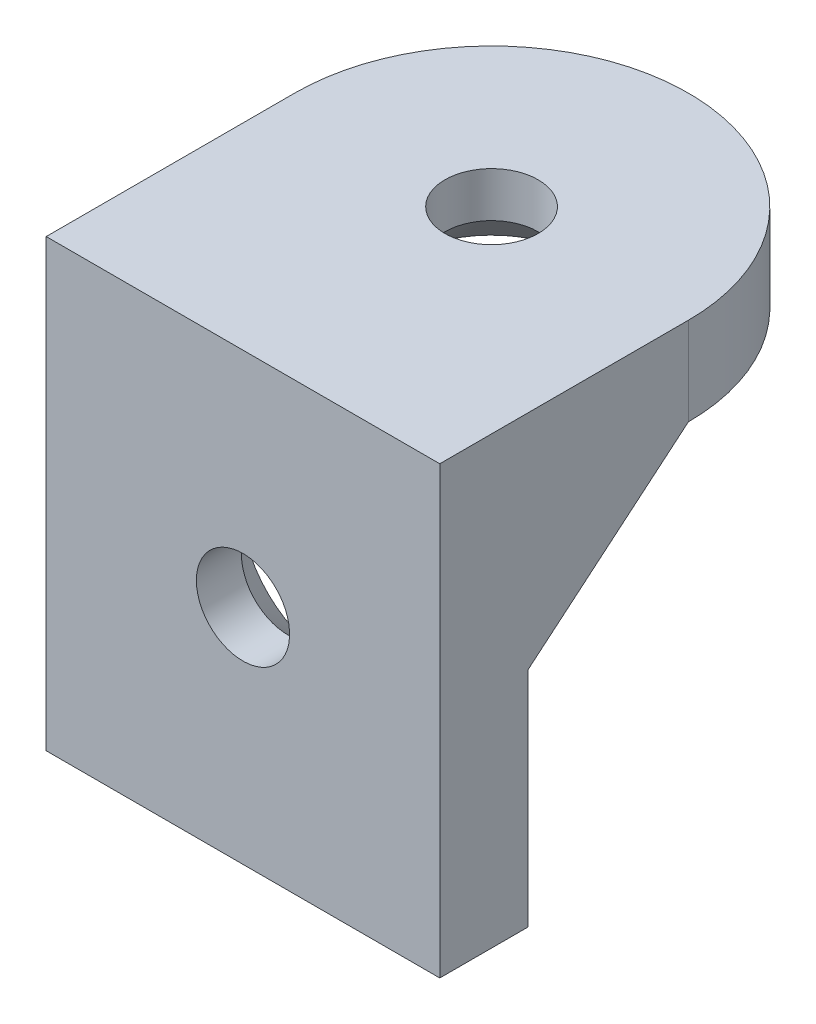
SolidWorks part; units mm, degrees
ref_plane "前视基准面" through (0, 0, 0) normal (0, 0, 1) x (1, 0, 0)
ref_plane "上视基准面" through (0, 0, 0) normal (0, 1, 0) x (1, 0, 0)
ref_plane "右视基准面" through (0, 0, 0) normal (1, 0, 0) x (0, 0, -1)
sketch "草图1" plane through (0, 0, 0) normal (0, 0, 1) x (1, 0, 0)
  line L1 (-19, -21.5) -> (19, -21.5)
  line L2 (-19, -21.5) -> (-19, 21.5)
  line L3 (-19, 21.5) -> (19, 21.5)
  line L4 (19, -21.5) -> (19, 21.5)
  line L5 (-19, -21.5) -> (19, 21.5) construction
  line L6 (-19, 21.5) -> (19, -21.5) construction
  point P0 (0, 0)
  dimension "D1" = 38
  dimension "D2" = 43
extrude "凸台-拉伸1" add sketch "草图1" along normal blind 8.5
sketch "草图2" plane through (0, 21.5, 0) normal (0, 1, 0) x (1, 0, 0)
  line L0 (-19, -8.5) -> (19, -8.5)
  line L1 (-19, -8.5) -> (-19, 15.5)
  line L2 (19, -8.5) -> (19, 15.5)
  arc A0 (-19, 15.5) -> (19, 15.5) centre (0, 15.5) cw
  dimension "D1" = 24
extrude "凸台-拉伸2" add sketch "草图2" against normal blind 8.5
sketch "草图5" plane through (19, 0, 0) normal (1, 0, 0) x (0, 0, -1)
  line L0 (15.5, 13) -> (0, 13)
  line L1 (0, 13) -> (0, 0)
  line L2 (0, 0) -> (15.5, 13)
extrude "凸台-拉伸3" add sketch "草图5" against normal blind 3.8
mirror "镜向1" about plane through (0, 0, 0) normal (1, 0, 0) of "凸台-拉伸3"
hole_wizard "M8 平锥沉头螺钉的锥形沉头孔1" positions "草图7" profile "草图6" countersink size "M8" standard "JIS" end condition through all
sketch "草图7" plane through (0, 0, 0) normal (0, 0, -1) x (-1, 0, 0)
  point P0 (0, 0)
sketch "草图6" plane through (0, 0, 0) normal (1, 0, 0) x (0, 1, 0)
  line L0 (0, 0) -> (0, 8.5)
  line L1 (0, 8.5) -> (4.5, 8.5)
  line L2 (4.5, 8.5) -> (4.5, 4.15)
  line L3 (4.5, 4.15) -> (8.65, 0)
  line L5 (8.65, 0) -> (0, 0)
  line L6 (-4.5, 4.15) -> (-8.65, 0) construction
  line L11 (0, -6.35) -> (0, 107.95) construction
  dimension "通孔孔直径" = 9
  dimension "通孔孔深度" = 8.5
  dimension "近端锥形沉头孔直径" = 17.3
  dimension "近端锥形沉头孔角度" = 90
hole_wizard "M8 平锥沉头螺钉的锥形沉头孔2" positions "草图9" profile "草图8" countersink size "M8" standard "JIS" end condition through all
sketch "草图9" plane through (0, 13, 0) normal (0, -1, 0) x (1, 0, 0)
  arc A0 (-19, -15.5) -> (19, -15.5) centre (0, -15.5) ccw construction
  arc A1 (-19, -15.5) -> (19, -15.5) centre (0, -15.5) ccw
  point P0 (0, -15.5)
sketch "草图8" plane through (0, 13, -15.5) normal (1, 0, 0) x (0, 0, -1)
  line L0 (0, 0) -> (0, 8.5)
  line L1 (0, 8.5) -> (4.5, 8.5)
  line L2 (4.5, 8.5) -> (4.5, 4.15)
  line L3 (4.5, 4.15) -> (8.65, 0)
  line L5 (8.65, 0) -> (0, 0)
  line L6 (-4.5, 4.15) -> (-8.65, 0) construction
  line L11 (0, -6.35) -> (0, 107.95) construction
  dimension "通孔孔直径" = 9
  dimension "通孔孔深度" = 8.5
  dimension "近端锥形沉头孔直径" = 17.3
  dimension "近端锥形沉头孔角度" = 90
